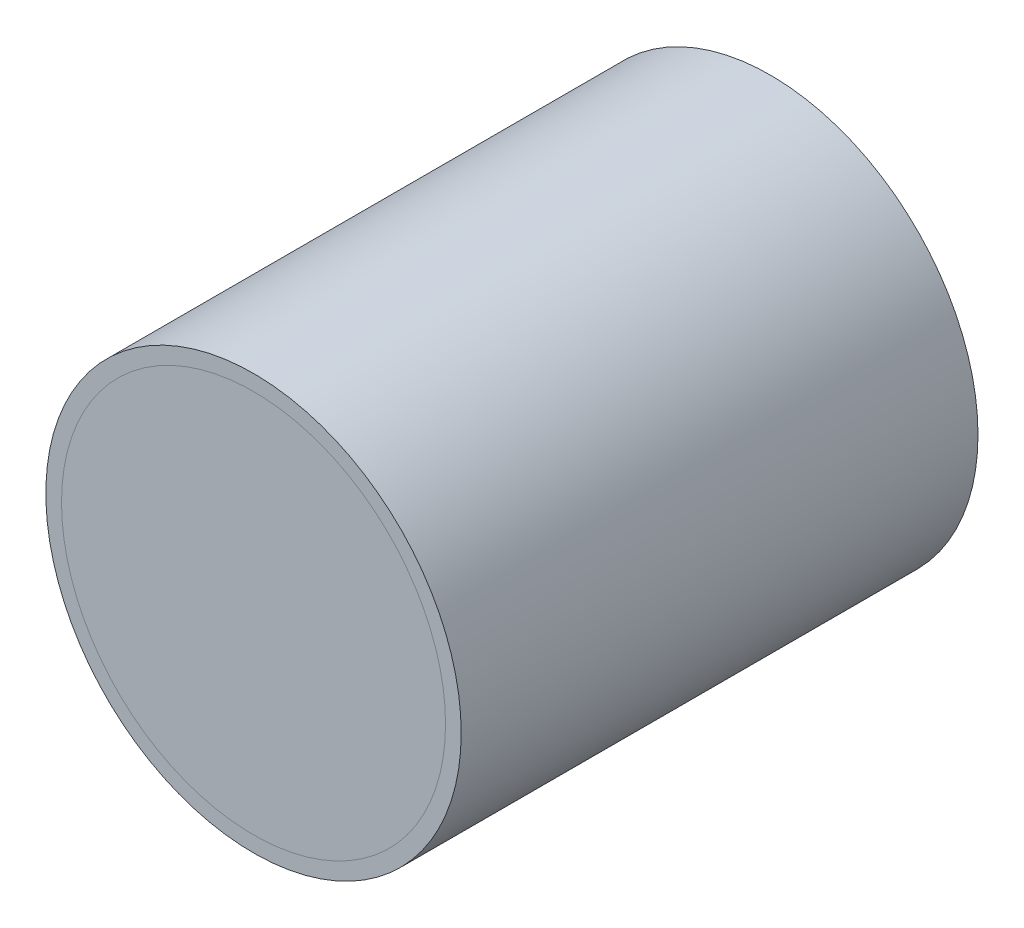
SolidWorks part; units mm, degrees
other "03155L"
other "8023D"
material "APCP"
ref_plane "Front Plane" through (0, 0, 0) normal (0, 0, 1) x (1, 0, 0)
ref_plane "Top Plane" through (0, 0, 0) normal (0, 1, 0) x (1, 0, 0)
ref_plane "Right Plane" through (0, 0, 0) normal (1, 0, 0) x (0, 0, -1)
sketch "Sketch1" plane through (0, 0, 0) normal (0, 0, 1) x (1, 0, 0)
  circle A0 centre (0, 0) radius 7.747
  circle A1 centre (0, 0) radius 7.1628
  dimension "D1" = 15.494
  dimension "D2" = 14.3256
extrude "Boss-Extrude1" add sketch "Sketch1" along normal blind 19.2786
sketch "Sketch2" plane through (0, 0, 0) normal (0, 0, 1) x (1, 0, 0)
  circle A0 centre (0, 0) radius 7.1628
  circle A1 centre (0, 0) radius 7.1628 construction
extrude "Boss-Extrude2" add sketch "Sketch2" along normal up to surface (19.2786 mm away) separate body up to face at (7.747, 0, 19.2786)
